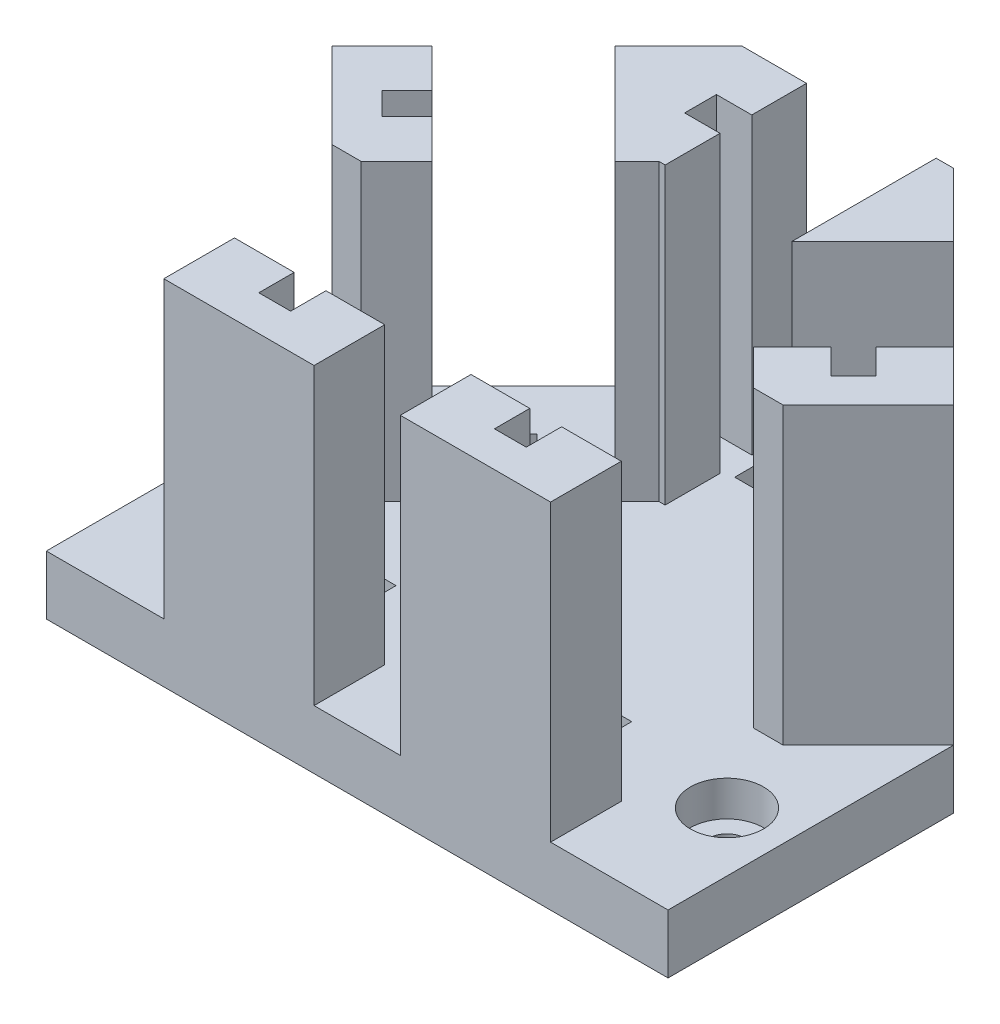
SolidWorks part; units mm, degrees
material "CA"
ref_plane "Front Plane" through (0, 0, 0) normal (0, 0, 1) x (1, 0, 0)
ref_plane "Top Plane" through (0, 0, 0) normal (0, 1, 0) x (1, 0, 0)
ref_plane "Right Plane" through (0, 0, 0) normal (1, 0, 0) x (0, 0, -1)
sketch "Sketch1" plane through (0, 0, 0) normal (0, 1, 0) x (1, 0, 0)
  line L0 (-6.5, 0) -> (6.5, 0) construction
  line L1 (-6.5, 0) -> (-20.0208, -13.5208) construction
  line L2 (0, 0) -> (0, -22.1581) construction
  line L3 (-26.0208, -11.7635) -> (-19.1421, -18.6421)
  line L4 (-26.0208, -11.7635) -> (-26.3848, -11.3995)
  line L5 (6.5, 0) -> (20.0208, -13.5208) construction
  line L6 (-3.5, 3) -> (-3.5, 5.9961)
  line L7 (-3.5, 5.9961) -> (-8.9892, 5.9961)
  line L10 (-3.5, -6.0039) -> (-3.5, -3)
  line L12 (-6.5, 1.35) -> (-6.5, -1.35)
  line L14 (-20.0208, -13.5208) -> (-20.9754, -12.5662)
  line L16 (-20.0208, -9.2782) -> (-22.1421, -7.1569)
  line L17 (-22.1421, -7.1569) -> (-26.3848, -11.3995)
  line L19 (-16.6569, -18.6421) -> (-13.6569, -15.6421)
  line L20 (-13.6569, -15.6421) -> (-15.7782, -13.5208)
  line L22 (-19.0662, -14.4754) -> (-20.0208, -13.5208)
  line L25 (-10, -32.6421) -> (-11.35, -32.6421)
  line L27 (-13.4146, -29.6421) -> (-16.4146, -29.6421)
  line L28 (-16.4146, -29.6421) -> (-16.4146, -35.6421)
  line L29 (-16.4146, -35.6421) -> (-3.6608, -35.6421)
  line L30 (-3.6608, -35.6421) -> (-3.6608, -29.6421)
  line L31 (-3.6608, -29.6421) -> (-6.6608, -29.6421)
  line L33 (-8.65, -32.6421) -> (-10, -32.6421)
  line L34 (-19.1421, -18.6421) -> (-16.6569, -18.6421)
  line L36 (-14.364, 0.6213) -> (-5.8787, -7.864)
  line L38 (-14.364, 0.6213) -> (-8.9892, 5.9961)
  line L39 (-5.8787, -7.864) -> (-4.0186, -6.0039)
  line L40 (-4.0186, -6.0039) -> (-3.5, -6.0039)
  line L80 (7.5, 5.9961) -> (7.5, -6.2426)
  line L81 (7.5, -6.2426) -> (14.364, 0.6213)
  line L82 (14.364, 0.6213) -> (8.9892, 5.9961)
  line L83 (7.5, 5.9961) -> (8.9892, 5.9961)
  line L95 (-3.5, 3) -> (-3.5, 1.35)
  line L96 (-3.5, 1.35) -> (-6.5, 1.35)
  line L97 (-3.5, -3) -> (-3.5, -1.35)
  line L98 (-3.5, -1.35) -> (-6.5, -1.35)
  line L99 (-20.0208, -9.2782) -> (-18.8541, -10.4449)
  line L100 (-18.8541, -10.4449) -> (-20.9754, -12.5662)
  line L101 (-15.7782, -13.5208) -> (-16.9449, -12.3541)
  line L102 (-16.9449, -12.3541) -> (-19.0662, -14.4754)
  line L103 (-13.4146, -29.6421) -> (-11.35, -29.6421)
  line L104 (-11.35, -29.6421) -> (-11.35, -32.6421)
  line L105 (-6.6608, -29.6421) -> (-8.65, -29.6421)
  line L106 (-8.65, -29.6421) -> (-8.65, -32.6421)
  line L107 (16.9449, -12.3541) -> (19.0662, -14.4754)
  line L108 (15.7782, -13.5208) -> (16.9449, -12.3541)
  line L109 (13.6569, -15.6421) -> (15.7782, -13.5208)
  line L110 (16.6569, -18.6421) -> (13.6569, -15.6421)
  line L111 (19.1421, -18.6421) -> (16.6569, -18.6421)
  line L112 (26.0208, -11.7635) -> (19.1421, -18.6421)
  line L113 (26.0208, -11.7635) -> (26.3848, -11.3995)
  line L114 (22.1421, -7.1569) -> (26.3848, -11.3995)
  line L115 (20.0208, -9.2782) -> (22.1421, -7.1569)
  line L116 (20.0208, -9.2782) -> (18.8541, -10.4449)
  line L117 (18.8541, -10.4449) -> (20.9754, -12.5662)
  line L118 (20.0208, -13.5208) -> (20.9754, -12.5662)
  line L119 (19.0662, -14.4754) -> (20.0208, -13.5208)
  line L120 (8.65, -29.6421) -> (8.65, -32.6421)
  line L121 (6.6608, -29.6421) -> (8.65, -29.6421)
  line L122 (3.6608, -29.6421) -> (6.6608, -29.6421)
  line L123 (3.6608, -35.6421) -> (3.6608, -29.6421)
  line L124 (16.4146, -35.6421) -> (3.6608, -35.6421)
  line L125 (16.4146, -29.6421) -> (16.4146, -35.6421)
  line L126 (13.4146, -29.6421) -> (16.4146, -29.6421)
  line L127 (13.4146, -29.6421) -> (11.35, -29.6421)
  line L128 (11.35, -29.6421) -> (11.35, -32.6421)
  line L129 (10, -32.6421) -> (11.35, -32.6421)
  line L130 (8.65, -32.6421) -> (10, -32.6421)
  point P2 (0, 0)
  dimension "D1" = 13
  dimension "D3" = 135
  dimension "D4" = 14
  dimension "D5" = 1.35
  dimension "D6" = 1.35
  dimension "D7" = 2.9961
  dimension "D8" = 1.35
  dimension "D9" = 1.35
  dimension "D10" = 1.35
  dimension "D11" = 3
  dimension "D12" = 1.35
  dimension "D15" = 3
  dimension "D17" = 3.0039
  dimension "D20" = 3
  dimension "D22" = 6
  dimension "D24" = 3
  dimension "D26" = 14
  dimension "D27" = 14
  dimension "D29" = 10
  dimension "D30" = 3
extrude "Boss-Extrude1" add sketch "Sketch1" along normal blind 25
sketch "Sketch2" plane through (0, 0, 0) normal (0, -1, 0) x (-1, 0, 0)
  line L0 (16.4146, -35.6421) -> (-16.4146, -35.6421)
  line L1 (-26.3848, -11.3995) -> (-8.9892, 5.9961)
  line L2 (-8.9892, 5.9961) -> (8.9892, 5.9961)
  line L3 (8.9892, 5.9961) -> (26.3848, -11.3995)
  line L4 (26.3848, -11.3995) -> (26.3848, -35.6421)
  line L5 (26.3848, -35.6421) -> (-16.4146, -35.6421)
  line L6 (-26.3848, -11.3995) -> (-26.3848, -35.6421)
  line L7 (-26.3848, -35.6421) -> (-16.4146, -35.6421)
extrude "Boss-Extrude2" add sketch "Sketch2" along normal blind 5 contours L5 L4 L3 L2 L1 L6 L7
sketch "Sketch3" plane through (0, 0, 0) normal (0, 1, 0) x (1, 0, 0)
  line L0 (-6.5, 0) -> (4.7384, 0) construction
  line L1 (-6.5, -1.35) -> (-6.5, 1.35) construction
  line L2 (0, 5.9961) -> (0, -35.6421) construction
  line L3 (7.5, 5.9961) -> (-3.5, 5.9961) construction
  line L4 (-3.6608, -35.6421) -> (3.6608, -35.6421) construction
  line L5 (-20.0208, -13.5208) -> (-12.06, -5.56) construction
  line L6 (-19.0662, -14.4754) -> (-20.9754, -12.5662) construction
  line L7 (-10, -32.6421) -> (-10, -21.1016) construction
  line L8 (-8.65, -32.6421) -> (-11.35, -32.6421) construction
  line L9 (-6.5, -1.35) -> (-6.5, 1.35) construction
  line L10 (-2.6, -1) -> (2.8, -1)
  line L11 (-2.6, -1) -> (-2.6, 1)
  line L12 (-2.6, 1) -> (2.8, 1)
  line L13 (2.8, -1) -> (2.8, 1)
  line L14 (-2.6, -1) -> (2.8, 1) construction
  line L15 (-2.6, 1) -> (2.8, -1) construction
  line L16 (-17.9702, -10.056) -> (-16.556, -11.4702)
  line L17 (-16.556, -11.4702) -> (-12.7376, -7.6518)
  line L18 (-12.7376, -7.6518) -> (-14.1518, -6.2376)
  line L19 (-14.1518, -6.2376) -> (-17.9702, -10.056)
  line L20 (-20.9754, -12.5662) -> (-18.8541, -10.4449) construction
  line L21 (11, -23.3421) -> (9, -23.3421)
  line L22 (-11, -28.7421) -> (-9, -28.7421)
  line L23 (-11, -28.7421) -> (-11, -23.3421)
  line L24 (-11, -23.3421) -> (-9, -23.3421)
  line L25 (-9, -28.7421) -> (-9, -23.3421)
  line L26 (-11, -28.7421) -> (-9, -23.3421) construction
  line L27 (-11, -23.3421) -> (-9, -28.7421) construction
  line L28 (9, -28.7421) -> (9, -23.3421)
  line L29 (11, -28.7421) -> (9, -28.7421)
  line L30 (11, -28.7421) -> (11, -23.3421)
  line L31 (12.7376, -7.6518) -> (14.1518, -6.2376)
  line L32 (16.556, -11.4702) -> (12.7376, -7.6518)
  line L33 (17.9702, -10.056) -> (16.556, -11.4702)
  line L34 (14.1518, -6.2376) -> (17.9702, -10.056)
  line L35 (-26.3848, -35.6421) -> (-16.4146, -35.6421) construction
  line L36 (-26.3848, -11.3995) -> (-26.3848, -35.6421) construction
  circle A0 centre (-21.3848, -25.6421) radius 1.55
  circle A1 centre (0, -23.6421) radius 1.55
  circle A2 centre (21.3848, -25.6421) radius 1.55
  point P19 (0.1, 0)
  point P28 (-17.2631, -10.7631)
  point P33 (-10, -26.0421)
  dimension "D11" = 10
  dimension "D12" = 5
  dimension "D13" = 3.1
  dimension "D14" = 3.1
  dimension "D1" = 5.4
  dimension "D2" = 3.9
  dimension "D3" = 2
  dimension "D4" = 2
  dimension "D5" = 5.4
  dimension "D6" = 3.9
  dimension "D7" = 2
  dimension "D8" = 3.9
  dimension "D9" = 5.4
  dimension "D10" = 12
extrude "Cut-Extrude1" cut sketch "Sketch3" against normal blind 5
sketch "Sketch4" plane through (0, 0, 0) normal (0, 1, 0) x (1, 0, 0)
  circle A0 centre (-21.3848, -25.6421) radius 3.1
  circle A1 centre (0, -23.6421) radius 3.1
  circle A2 centre (21.3848, -25.6421) radius 3.1
  dimension "D1" = 6.2
extrude "Cut-Extrude2" cut sketch "Sketch4" against normal blind 3
